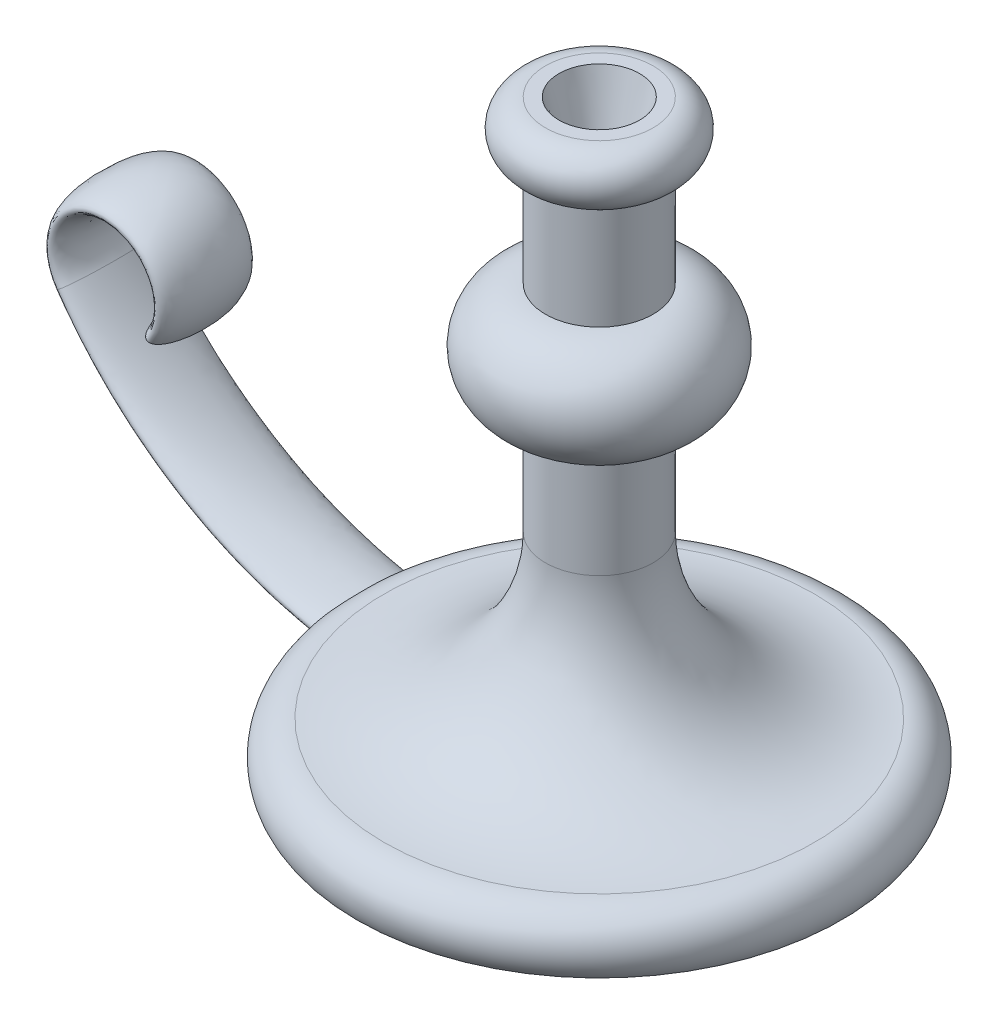
SolidWorks part; units mm, degrees
ref_plane "Front Plane" through (0, 0, 0) normal (0, 0, 1) x (1, 0, 0)
ref_plane "Top Plane" through (0, 0, 0) normal (0, 1, 0) x (1, 0, 0)
ref_plane "Right Plane" through (0, 0, 0) normal (1, 0, 0) x (0, 0, -1)
sketch "Sketch1" plane through (0, 0, 0) normal (0, 0, 1) x (1, 0, 0)
  line L0 (0, 220) -> (20, 220)
  line L1 (90, 0) -> (0, 0)
  line L2 (0, 0) -> (0, 220)
  line L3 (20, 200) -> (20, 160)
  line L4 (20, 120) -> (20, 80)
  arc A0 (20, 220) -> (20, 200) centre (20, 210) cw
  arc A1 (20, 160) -> (20, 120) centre (20, 140) cw
  arc A4 (20, 80) -> (80, 20) centre (80, 80) ccw
  arc A5 (80, 20) -> (90, 0) centre (80, 7.5) cw
  dimension "D4" = 10
  dimension "D5" = 20
  dimension "D7" = 40
  dimension "D8" = 12.5
  dimension "D9" = 60
  dimension "D1" = 20
  dimension "D2" = 220
  dimension "D3" = 90
  dimension "D6" = 40
  dimension "D10" = 80
  dimension "D11" = 20
revolve "Revolve1" add sketch "Sketch1" angle 360 about L2
sketch "Sketch2" plane through (0, 0, 0) normal (0, 0, 1) x (1, 0, 0)
  line L0 (0, 10) -> (-60, 10)
  line L1 (0, 126.8188) -> (0, -13.6376) construction
  line L2 (-90, 0) -> (90, 0) construction
  arc A0 (-60, 10) -> (-183.5921, 75) centre (-60, 160) cw
  arc A1 (-183.5921, 75) -> (-150.6342, 75) centre (-167.1131, 86.3333) cw
  point P10 (0, 0)
  dimension "D2" = 20
  dimension "D4" = 150
  dimension "D5" = 75
  dimension "D8" = 60
  dimension "D1" = 10
  dimension "D3" = 65
  dimension "D6" = 32.9579
  dimension "D7" = 150.6342
sketch "Sketch4" plane through (0, 0, 0) normal (1, 0, 0) x (0, 0, -1)
  ellipse E0 centre (0, 10) end of major axis (-17.5, 10) minor radius 5
  dimension "D1" = 35
  dimension "D2" = 10
sweep "Sweep1" add profiles "Sketch4" path "Sketch2"
sketch "Sketch5" plane through (0, 220, 0) normal (0, 1, 0) x (1, 0, 0)
  circle A0 centre (0, 0) radius 15
  dimension "D1" = 30
extrude "Cut-Extrude2" cut sketch "Sketch5" against normal blind 25 draft 15
